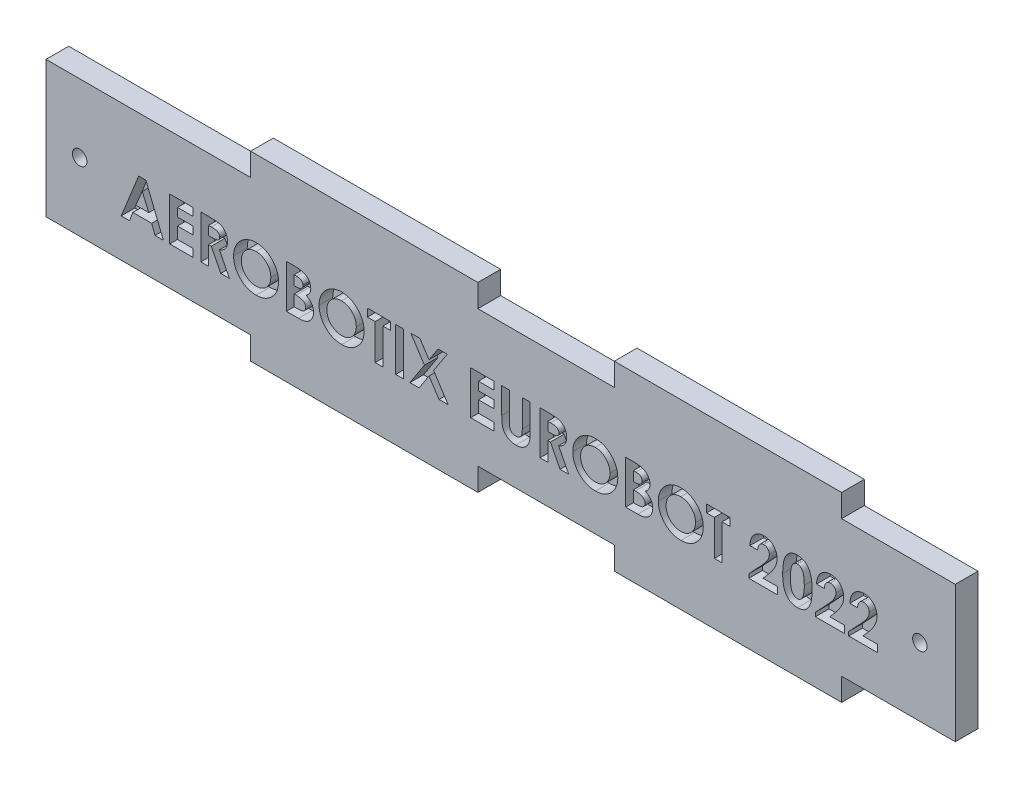
SolidWorks part; units mm, degrees
material "Acrylique (impact moyen-haut)"
ref_plane "Plan de face" through (0, 0, 0) normal (0, 0, 1) x (1, 0, 0)
ref_plane "Plan de dessus" through (0, 0, 0) normal (0, 1, 0) x (1, 0, 0)
ref_plane "Plan de droite" through (0, 0, 0) normal (1, 0, 0) x (0, 0, -1)
sketch "Esquisse1" plane through (0, 0, 0) normal (0, 0, 1) x (1, 0, 0)
  line L0 (-155, 30) -> (-155, 35)
  line L1 (0, 0) -> (-25, 0)
  line L2 (0, 0) -> (0, 30)
  line L3 (0, 30) -> (-25, 30)
  line L4 (-200, 0) -> (-200, 30)
  line L5 (-155, 35) -> (-105, 35)
  line L6 (-105, 35) -> (-105, 30)
  line L7 (-155, 30) -> (-200, 30)
  line L8 (-75, 35) -> (-25, 35)
  line L9 (-75, 30) -> (-75, 35)
  line L10 (-25, 35) -> (-25, 30)
  line L11 (-75, 30) -> (-105, 30)
  line L12 (-200, 15) -> (0, 15) construction
  line L13 (-25, -5) -> (-25, 0)
  line L14 (-75, -5) -> (-25, -5)
  line L15 (-75, 0) -> (-75, -5)
  line L16 (-105, -5) -> (-105, 0)
  line L17 (-155, 0) -> (-155, -5)
  line L18 (-155, -5) -> (-105, -5)
  line L19 (-155, 0) -> (-200, 0)
  line L20 (-75, 0) -> (-105, 0)
  circle A0 centre (-192.6, 15) radius 1.6
  circle A1 centre (-7.8, 15) radius 1.5893
  dimension "D1" = 30
  dimension "D2" = 200
  dimension "D3" = 50
  dimension "D4" = 5
  dimension "D5" = 45
  dimension "D6" = 2
extrude "Boss.-Extru.1" add sketch "Esquisse1" along normal blind 5
sketch "Esquisse2" plane through (0, 0, 5) normal (0, 0, 1) x (1, 0, 0)
  line L0 (-200, 8.4375) -> (0, 8.4375) construction
  line L3 (-200, 30) -> (-200, 0) construction
  line L4 (0, 0) -> (0, 30) construction
  text T0 "AEROBOTIX EUROBOT 2022" font "Century Gothic" height in points 36
extrude "Enlèv. mat.-Extru.1" cut sketch "Esquisse2" against normal blind 3
sketch "Esquisse3" plane through (0, 0, 0) normal (0, 0, -1) x (-1, 0, 0)
  line L0 (0, 15) -> (200, 15) construction
  line L1 (0, 0) -> (0, 30) construction
  line L2 (200, 30) -> (200, 0) construction
  text T0 "<b>AEROBOTIX EUROBOT 2022</b>" font "Century Gothic" height in points 36
extrude "Enlèv. mat.-Extru.2" cut sketch "Esquisse3" against normal blind 1
